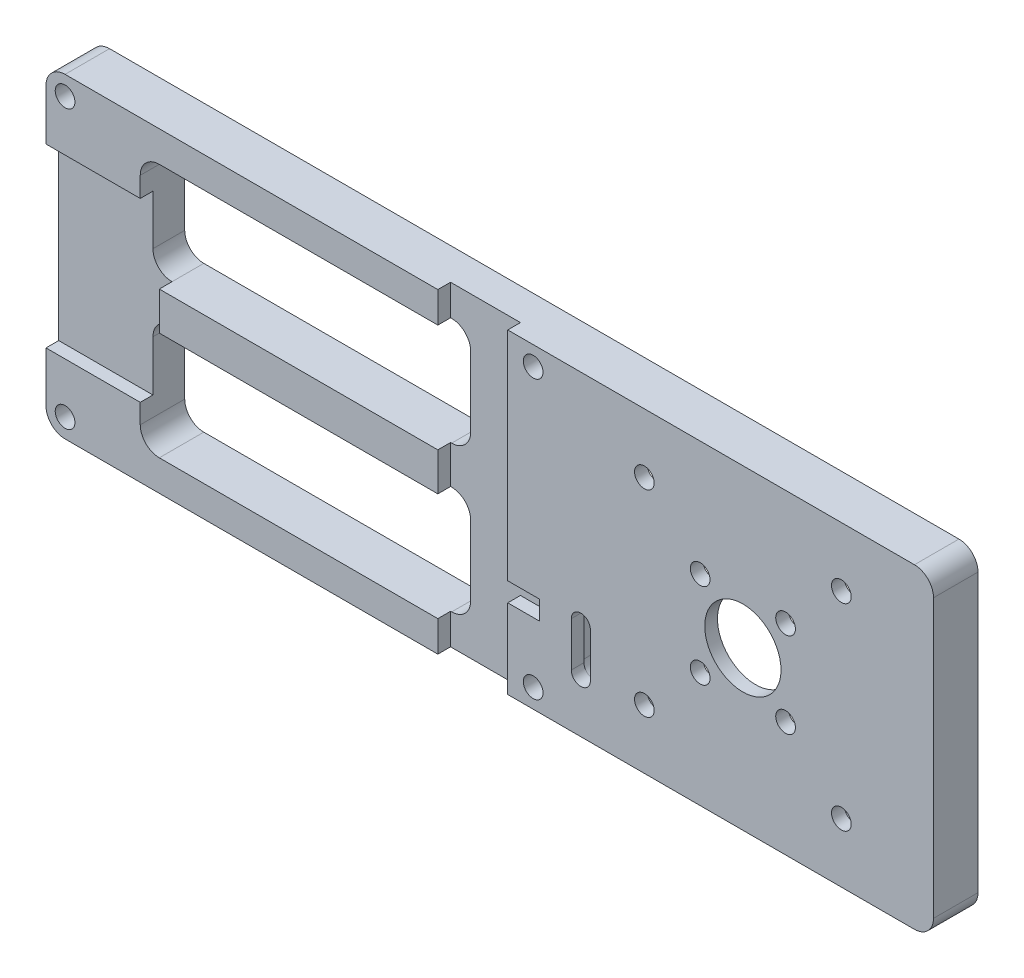
SolidWorks part; units mm, degrees
ref_plane "前视基准面" through (0, 0, 0) normal (0, 0, 1) x (1, 0, 0)
ref_plane "上视基准面" through (0, 0, 0) normal (0, 1, 0) x (1, 0, 0)
ref_plane "右视基准面" through (0, 0, 0) normal (1, 0, 0) x (0, 0, -1)
sketch "草图1" plane through (0, 0, 0) normal (0, 0, 1) x (1, 0, 0)
  line L4 (11.83, -15.844) -> (11.83, -4.844)
  line L5 (0, 3) -> (73.66, 3)
  line L7 (73.66, -46.688) -> (0, -46.688)
  line L8 (-3, -43.688) -> (-3, 0)
  line L9 (136.66, -21.844) -> (136.66, 0)
  line L10 (133.66, 3) -> (73.66, 3)
  line L11 (136.66, -21.844) -> (136.66, -43.688)
  line L12 (133.66, -46.688) -> (73.66, -46.688)
  line L15 (36.83, -41.844) -> (58.83, -41.844)
  line L16 (36.83, -41.844) -> (14.83, -41.844)
  line L17 (11.83, -38.844) -> (11.83, -27.844)
  line L18 (14.83, -1.844) -> (36.83, -1.844)
  line L19 (36.83, -1.844) -> (58.83, -1.844)
  line L20 (61.83, -4.844) -> (61.83, -15.844)
  line L21 (61.83, -27.844) -> (61.83, -38.844)
  line L23 (36.83, -18.844) -> (58.83, -18.844)
  line L24 (36.83, -18.844) -> (14.83, -18.844)
  line L25 (36.83, -24.844) -> (58.83, -24.844)
  line L26 (36.83, -24.844) -> (14.83, -24.844)
  circle A0 centre (0, 0) radius 1.55
  circle A1 centre (73.66, 0) radius 1.55
  circle A2 centre (0, -43.688) radius 1.55
  circle A3 centre (73.66, -43.688) radius 1.55
  arc A4 (0, 3) -> (-3, 0) centre (0, 0) ccw
  arc A5 (-3, -43.688) -> (0, -46.688) centre (0, -43.688) ccw
  arc A8 (136.66, -43.688) -> (133.66, -46.688) centre (133.66, -43.688) cw
  arc A9 (136.66, 0) -> (133.66, 3) centre (133.66, 0) ccw
  arc A10 (14.83, -41.844) -> (11.83, -38.844) centre (14.83, -38.844) cw
  arc A11 (58.83, -1.844) -> (61.83, -4.844) centre (58.83, -4.844) cw
  arc A12 (11.83, -4.844) -> (14.83, -1.844) centre (14.83, -4.844) cw
  arc A13 (58.83, -41.844) -> (61.83, -38.844) centre (58.83, -38.844) ccw
  arc A14 (14.83, -24.844) -> (11.83, -27.844) centre (14.83, -27.844) ccw
  arc A15 (58.83, -24.844) -> (61.83, -27.844) centre (58.83, -27.844) cw
  arc A16 (58.83, -18.844) -> (61.83, -15.844) centre (58.83, -15.844) ccw
  arc A17 (14.83, -18.844) -> (11.83, -15.844) centre (14.83, -15.844) cw
  circle A18 centre (106.66, -21.844) radius 6
  circle A32 centre (91.16, -6.344) radius 1.55
  circle A33 centre (91.16, -37.344) radius 1.55
  circle A34 centre (122.16, -37.344) radius 1.55
  circle A35 centre (122.16, -6.344) radius 1.55
  circle A36 centre (99.9425, -15.1265) radius 1.55
  circle A37 centre (113.3775, -15.1265) radius 1.55
  circle A38 centre (113.3775, -28.5615) radius 1.55
  circle A39 centre (99.9425, -28.5615) radius 1.55
  point P31 (11.83, -41.844)
  point P37 (61.83, -41.844)
  point P48 (61.83, -24.844)
  point P53 (11.83, -18.844)
  point P67 (106.66, -21.844)
  point P76 (106.66, -21.844)
  point P77 (106.66, -21.844)
  dimension "D1" = 3.1
  dimension "D4" = 3.1
  dimension "D5" = 3.1
  dimension "D6" = 3.1
  dimension "D8" = 6
  dimension "D9" = 6
  dimension "D10" = 3
  dimension "D11" = 25
  dimension "D12" = 3
  dimension "D7" = 3
  dimension "D14" = 3
  dimension "D16" = 12
  dimension "D17" = 9.5
  dimension "D18" = 3.1
  dimension "D19" = 3.1
  dimension "D2" = 43.688
  dimension "D3" = 73.66
  dimension "D13" = 25
  dimension "D15" = 30
  dimension "D20" = 4
extrude "凸台-拉伸1" add sketch "草图1" along normal blind 7
sketch "草图2" plane through (0, 0, 7) normal (0, 0, 1) x (1, 0, 0)
  line L0 (1.9331, -8) -> (11.83, -8)
  line L4 (-3, 0) -> (-3, -43.688) construction
  line L5 (1.9331, -8) -> (-3, -8)
  line L6 (11.83, -4.844) -> (11.83, -15.844) construction
  line L7 (11.83, -8) -> (11.83, -15.844)
  line L8 (-3, -8) -> (-3, -23)
  line L10 (1.9331, -35.7799) -> (-3, -35.7799)
  line L11 (69.66, -21.844) -> (69.66, 3)
  line L12 (69.66, 3) -> (67.66, 3)
  line L13 (58.66, -21.89) -> (58.66, 3)
  line L14 (133.66, 3) -> (0, 3) construction
  line L15 (58.66, 3) -> (67.66, 3)
  line L17 (0, -46.688) -> (133.66, -46.688) construction
  line L18 (67.66, -46.688) -> (58.66, -46.688)
  line L19 (58.66, -46.688) -> (58.66, -21.89)
  line L20 (69.66, -21.844) -> (69.66, -46.688)
  line L21 (69.66, -46.688) -> (67.66, -46.688)
  line L22 (1.9331, -35.7799) -> (11.83, -35.7799)
  line L23 (-3, -35.7799) -> (-3, -23)
  line L24 (11.83, -35.7799) -> (11.83, -27.844)
  line L25 (14.83, -23) -> (14.83, -18.844)
  line L26 (14.83, -23) -> (14.83, -24.844)
  arc A0 (14.83, -24.844) -> (11.83, -27.844) centre (14.83, -27.844) ccw construction
  arc A1 (11.83, -15.844) -> (14.83, -18.844) centre (14.83, -15.844) ccw construction
  arc A2 (14.83, -24.844) -> (11.83, -27.844) centre (14.83, -27.844) ccw
  arc A3 (11.83, -15.844) -> (14.83, -18.844) centre (14.83, -15.844) ccw
  dimension "D3" = 9
extrude "切除-拉伸3" cut sketch "草图2" against normal blind 2
sketch "草图4" plane through (0, 0, 0) normal (0, 0, -1) x (-1, 0, 0)
  circle A4 centre (-73.66, 0) radius 2.5
  circle A5 centre (-73.66, -43.688) radius 2.5
  circle A6 centre (0, 0) radius 2.5
  circle A7 centre (0, -43.688) radius 2.5
  dimension "D5" = 5
  dimension "D6" = 5
  dimension "D7" = 5
  dimension "D8" = 5
extrude "切除-拉伸4" cut sketch "草图4" against normal blind 3
sketch "草图5" plane through (0, 0, 0) normal (0, 0, -1) x (-1, 0, 0)
  line L5 (-85.41, -3.594) -> (-81.41, -3.594)
  line L6 (-124.91, -43.094) -> (-88.41, -43.094)
  line L11 (-127.91, -40.094) -> (-127.91, -3.594)
  line L12 (-124.91, -0.594) -> (-88.41, -0.594)
  line L14 (-127.91, -43.094) -> (-85.41, -0.594) construction
  line L15 (-127.91, -0.594) -> (-85.41, -43.094) construction
  line L16 (-79.41, -5.594) -> (-79.41, -37.094)
  line L18 (-85.41, -40.094) -> (-81.41, -40.094)
  line L19 (-79.41, -38.094) -> (-79.41, -37.094)
  arc A6 (-88.41, -0.594) -> (-85.41, -3.594) centre (-88.41, -3.594) cw
  arc A7 (-88.41, -43.094) -> (-85.41, -40.094) centre (-88.41, -40.094) ccw
  arc A8 (-124.91, -43.094) -> (-127.91, -40.094) centre (-124.91, -40.094) cw
  arc A9 (-127.91, -3.594) -> (-124.91, -0.594) centre (-124.91, -3.594) cw
  arc A10 (-81.41, -3.594) -> (-79.41, -5.594) centre (-81.41, -5.594) cw
  arc A12 (-81.41, -40.094) -> (-79.41, -38.094) centre (-81.41, -38.094) ccw
  point P0 (-106.66, -21.844)
  point P22 (-79.41, -3.594)
  dimension "D3" = 3
  dimension "D6" = 2
  dimension "D5" = 2
  dimension "D1" = 42.5
  dimension "D2" = 42.5
  dimension "D4" = 6
extrude "切除-拉伸5" cut sketch "草图5" against normal blind 5
sketch "草图6" plane through (0, 0, 5) normal (0, 0, -1) x (-1, 0, 0)
  line L1 (-82.66, -31.344) -> (-82.66, -38.344)
  line L2 (-79.66, -31.344) -> (-79.66, -38.344)
  arc A1 (-79.66, -31.344) -> (-82.66, -31.344) centre (-81.16, -31.344) ccw
  arc A2 (-82.66, -38.344) -> (-79.66, -38.344) centre (-81.16, -38.344) ccw
  dimension "D3" = 3
extrude "切除-拉伸6" cut sketch "草图6" against normal blind 2
sketch "草图7" plane through (0, 0, 7) normal (0, 0, 1) x (1, 0, 0)
  line L2 (74.66, -31.188) -> (74.66, -34.188)
  line L3 (74.66, -31.188) -> (69.66, -31.188)
  line L4 (69.66, -46.688) -> (69.66, 3) construction
  line L5 (69.66, -31.188) -> (69.66, -34.188)
  line L6 (69.66, -46.688) -> (69.66, 3) construction
  line L7 (69.66, -34.188) -> (74.66, -34.188)
extrude "切除-拉伸7" cut sketch "草图7" against normal blind 2
